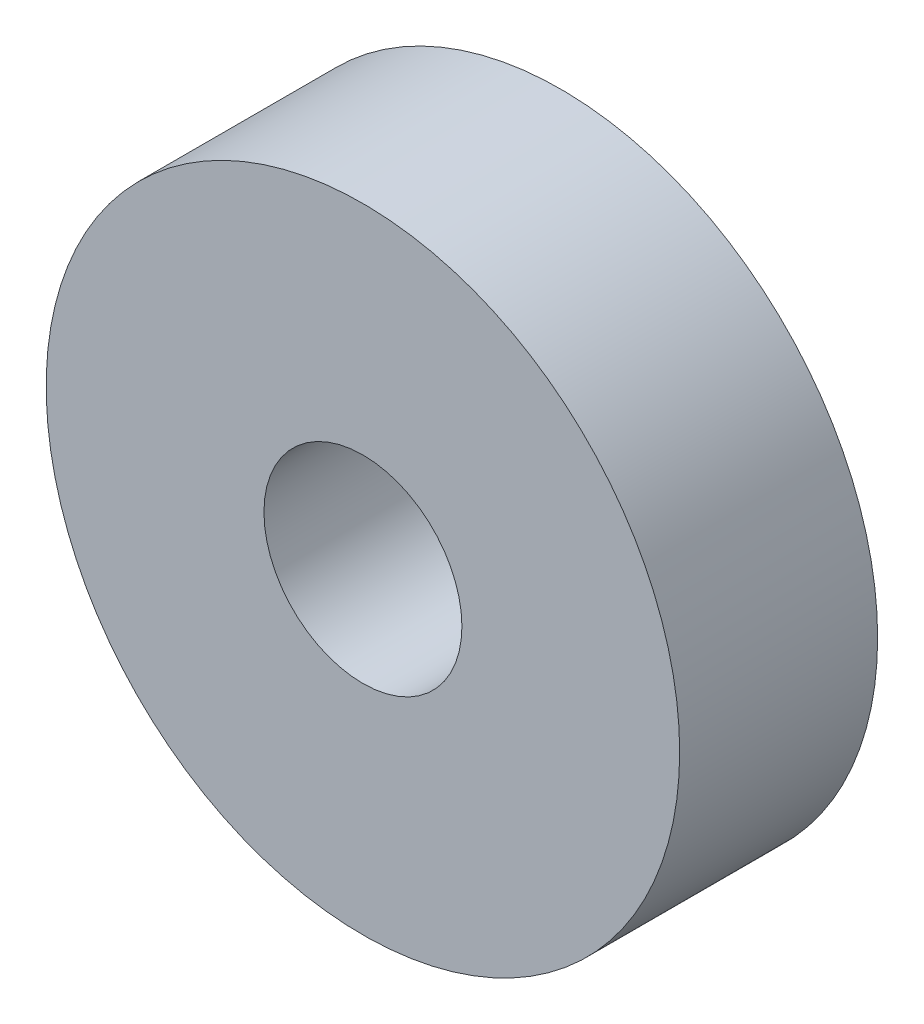
SolidWorks part; units mm, degrees
ref_plane "Front Plane" through (0, 0, 0) normal (1, 0, 0) x (0, 1, 0)
ref_plane "Top Plane" through (0, 0, 0) normal (0, 0, 1) x (0, 1, 0)
ref_plane "Right Plane" through (0, 0, 0) normal (0, 1, 0) x (-1, 0, 0)
sketch "Sketch1" plane through (0, 0, 0) normal (0, 0, 1) x (0, 1, 0)
  circle A0 centre (0, 0) radius 2.5
  circle A1 centre (0, 0) radius 8
  dimension "D1" = 5
  dimension "D2" = 16
extrude "Boss-Extrude1" add sketch "Sketch1" along normal blind 5
